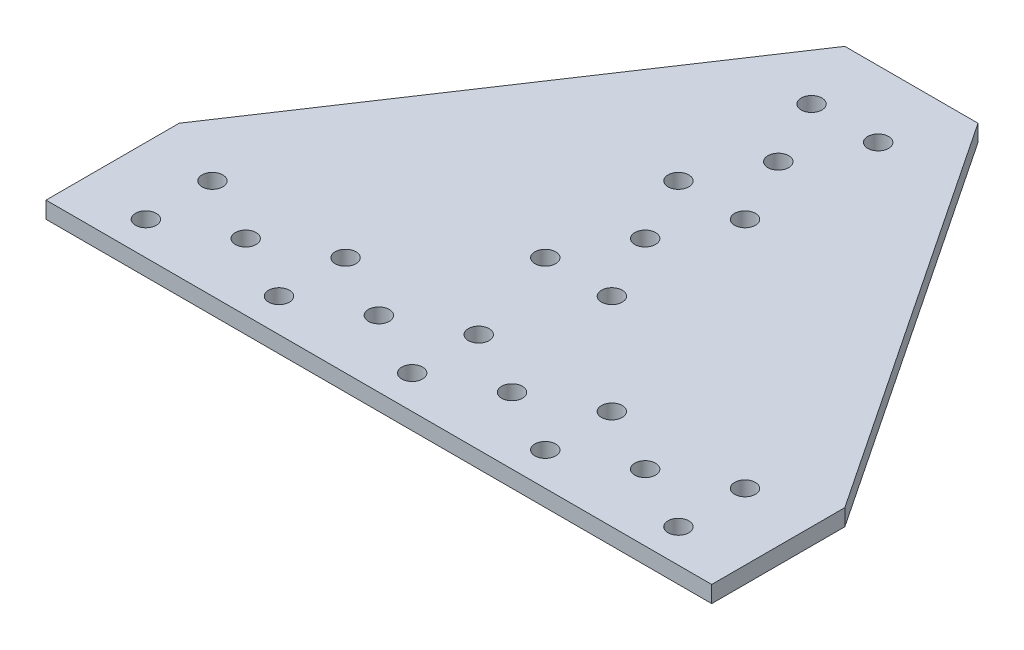
SolidWorks part; units mm, degrees
ref_plane "Front Plane" through (0, 0, 0) normal (0, 0, 1) x (1, 0, 0)
ref_plane "Top Plane" through (0, 0, 0) normal (0, 1, 0) x (1, 0, 0)
ref_plane "Right Plane" through (0, 0, 0) normal (1, 0, 0) x (0, 0, -1)
sketch "Sketch1" plane through (0, 0, 0) normal (0, 1, 0) x (1, 0, 0)
  line L0 (0, 101.6) -> (0, 0) construction
  line L1 (-12.7, 101.6) -> (12.7, 101.6)
  line L2 (12.7, 101.6) -> (63.5, 25.4)
  line L3 (63.5, 25.4) -> (63.5, 0)
  line L4 (63.5, 0) -> (-63.5, 0)
  line L5 (-63.5, 25.4) -> (-63.5, 0)
  line L6 (-12.7, 101.6) -> (-63.5, 25.4)
  circle A0 centre (6.35, 88.9) radius 1.9844
  circle A1 centre (6.35, 63.5) radius 1.9844
  circle A2 centre (6.35, 38.1) radius 1.9844
  circle A3 centre (12.7, 12.7) radius 1.9844
  circle A4 centre (25.4, 6.35) radius 1.9844
  circle A5 centre (25.4, 19.05) radius 1.9844
  circle A6 centre (38.1, 12.7) radius 1.9844
  circle A7 centre (50.8, 6.35) radius 1.9844
  circle A8 centre (50.8, 19.05) radius 1.9844
  circle A9 centre (0, 76.2) radius 1.9844
  circle A10 centre (0, 50.8) radius 1.9844
  circle A11 centre (0, 19.05) radius 1.9844
  circle A12 centre (0, 6.35) radius 1.9844
  circle A13 centre (-50.8, 19.05) radius 1.9844
  circle A14 centre (-50.8, 6.35) radius 1.9844
  circle A15 centre (-38.1, 12.7) radius 1.9844
  circle A16 centre (-25.4, 19.05) radius 1.9844
  circle A17 centre (-25.4, 6.35) radius 1.9844
  circle A18 centre (-12.7, 12.7) radius 1.9844
  circle A19 centre (-6.35, 38.1) radius 1.9844
  circle A20 centre (-6.35, 63.5) radius 1.9844
  circle A21 centre (-6.35, 88.9) radius 1.9844
  dimension "D5" = 3.9687
  dimension "D1" = 12.7
  dimension "D2" = 91.581
  dimension "D3" = 25.4
  dimension "D4" = 63.5
extrude "Boss-Extrude1" add sketch "Sketch1" along normal blind 3.175
